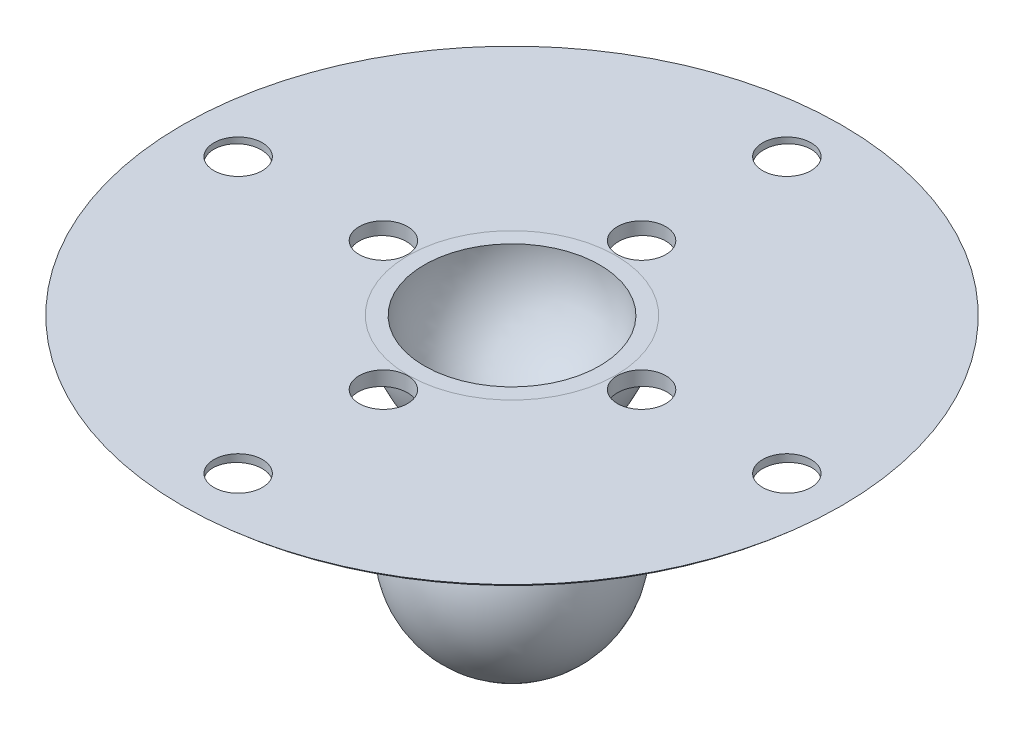
SolidWorks part; units mm, degrees
ref_plane "Front Plane" through (0, 0, 0) normal (0, 0, 1) x (1, 0, 0)
ref_plane "Top Plane" through (0, 0, 0) normal (0, 1, 0) x (1, 0, 0)
ref_plane "Right Plane" through (0, 0, 0) normal (1, 0, 0) x (0, 0, -1)
sketch "Sketch1" plane through (0, 0, 0) normal (1, 0, 0) x (0, 0, -1)
  line L0 (0.0008, 24.4665) -> (0.0003, 7.1) construction
  line L2 (0.0003, 7.1) -> (0.0002, 3.2) construction
  line L3 (0.0002, 3.2) -> (-0.0006, -23.2665) construction
  line L4 (3.2002, 3.2) -> (10.2002, 3.2)
  line L5 (3.1665, 2.737) -> (10.0428, 3.0622)
  line L6 (10.2002, 3.2) -> (10.0428, 3.0622)
  line L7 (0, 0.5) -> (-0.0002, -0.5)
  line L8 (0, -5.5) -> (-0.0001, -6)
  line L9 (2.7002, 3.2) -> (3.2002, 3.2)
  line L10 (1.0092, 0.1633) -> (1.2605, -0.2777)
  line L11 (-0.0152, 10.3413) -> (-0.0154, -16.5251) construction
  arc A0 (-0.0001, -6) -> (1.2605, -0.2777) centre (-0.0001, -3) ccw
  arc A2 (0, 0) -> (0.0001, 0) centre (0.0002, 3.2) ccw
  arc A3 (0, -5.5) -> (-0.0002, -0.5) centre (-0.0001, -3) ccw
  arc A4 (0, 0.5) -> (2.7002, 3.2) centre (0.0002, 3.2) ccw
  arc A5 (0.0001, 0) -> (1.0092, 0.1633) centre (0.0002, 3.2) ccw construction
  arc A6 (1.0092, 0.1633) -> (3.1665, 2.737) centre (0.0002, 3.2) ccw
  arc A7 (1.2605, -0.2777) -> (0.0001, 0) centre (-0.0001, -3) ccw construction
  arc A8 (0.0001, 0) -> (0, 0) centre (-0.0001, -3) ccw
  arc A9 (3.1665, 2.737) -> (3.2002, 3.2) centre (0.0002, 3.2) ccw construction
  dimension "D1" = 6
  dimension "D2" = 3.2
  dimension "D4" = 2.5
  dimension "D5" = 2.7
  dimension "D6" = 3
  dimension "D3" = 7
revolve "Revolve5" add sketch "Sketch1" angle 360 about L11
ref_plane "Plane1" through (0, 3.2001, 0) normal (0, 1, 0) x (1, 0, 0)
sketch "Sketch2" plane through (0, 3.2001, 0) normal (0, 1, 0) x (1, 0, 0)
  line L0 (-10.2154, 0) -> (10.2154, 0) construction
  line L1 (0, 10.2307) -> (0, -10.2307) construction
  circle A0 centre (0, 0) radius 0.75
  circle A1 centre (0, -0.0153) radius 10.2154 construction
  circle A2 centre (-4, 0) radius 0.75
  circle A3 centre (-8.5, 0) radius 0.75
  circle A4 centre (0, -4) radius 0.75
  circle A5 centre (0, -8.5) radius 0.75
  circle A6 centre (0, -0.0153) radius 3.2154 construction
  circle A7 centre (0, 8.5) radius 0.75
  circle A8 centre (0, 4) radius 0.75
  circle A9 centre (8.5, 0) radius 0.75
  circle A10 centre (4, 0) radius 0.75
  point P6 (0, 0)
  point P8 (0, 0)
  dimension "D1" = 1.5
  dimension "D2" = 4
  dimension "D4" = 1.5
  dimension "D5" = 1.5
  dimension "D8" = 1.5
  dimension "D9" = 1.5
  dimension "D3" = 8.5
  dimension "D6" = 4
  dimension "D7" = 8.5
extrude "Cut-Extrude1" cut sketch "Sketch2" against normal blind 13
